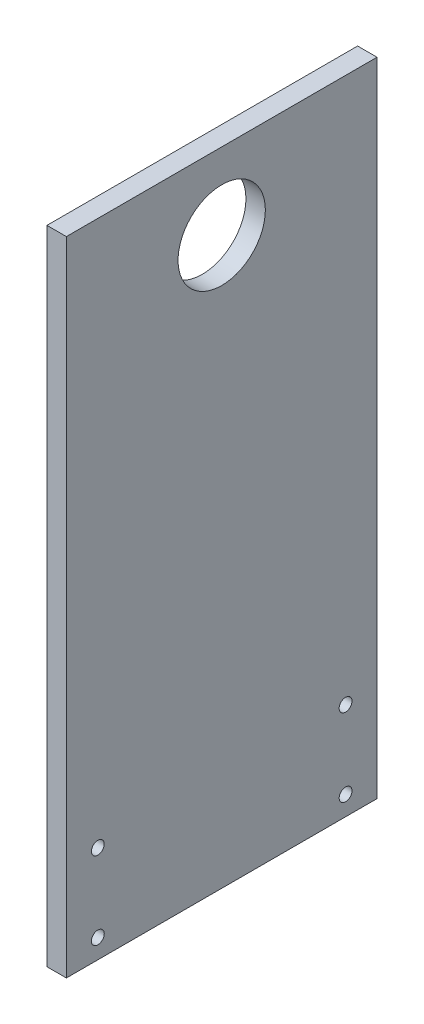
SolidWorks part; units mm, degrees
ref_plane "Plan de face" through (0, 0, 0) normal (0, 0, 1) x (1, 0, 0)
ref_plane "Plan de dessus" through (0, 0, 0) normal (0, 1, 0) x (1, 0, 0)
ref_plane "Plan de droite" through (0, 0, 0) normal (1, 0, 0) x (0, 0, -1)
sketch "Sketch1" plane through (0, 0, 0) normal (1, 0, 0) x (0, 0, -1)
  line L0 (-50.8, -66.9) -> (50.8, -66.9) construction
  line L1 (-50.8, 105) -> (50.8, 105)
  line L2 (-50.8, 105) -> (-50.8, -105)
  line L3 (-50.8, -105) -> (50.8, -105)
  line L4 (50.8, 105) -> (50.8, -105)
  line L5 (-50.8, 105) -> (50.8, -105) construction
  line L6 (-50.8, -105) -> (50.8, 105) construction
  line L7 (0, -66.9) -> (0, -105) construction
  line L8 (-40.513, -98.65) -> (40.513, -98.65) construction
  line L9 (-40.513, -98.65) -> (-40.513, -73.25) construction
  line L10 (-40.513, -73.25) -> (40.513, -73.25) construction
  line L11 (40.513, -98.65) -> (40.513, -73.25) construction
  circle A0 centre (-40.513, -98.65) radius 2.1
  circle A1 centre (40.513, -98.65) radius 2.1
  circle A10 centre (0, 80) radius 14.275
  circle A11 centre (-40.513, -73.25) radius 2.1
  circle A12 centre (40.513, -73.25) radius 2.1
  point P0 (0, 0)
  dimension "D3" = 4.2
  dimension "D4" = 4.2
  dimension "D24" = 28.55
  dimension "D10" = 4.2
  dimension "D11" = 4.2
  dimension "D1" = 210
  dimension "D2" = 101.6
  dimension "D9" = 38.1
  dimension "D25" = 25
  dimension "D26" = 50.8
  dimension "D5" = 6.35
  dimension "D6" = 6.35
  dimension "D7" = 40.513
  dimension "D8" = 40.513
extrude "Boss-Extrude1" add sketch "Sketch1" along normal blind 6.35
equation "\"D4@Sketch1\"=\"D3@Sketch1\""
equation "\"D7@Sketch1\"=3.19in/2"
equation "\"D8@Sketch1\"=\"D7@Sketch1\""
equation "\"D10@Sketch1\"=\"D3@Sketch1\""
equation "\"D11@Sketch1\"=\"D3@Sketch1\""
